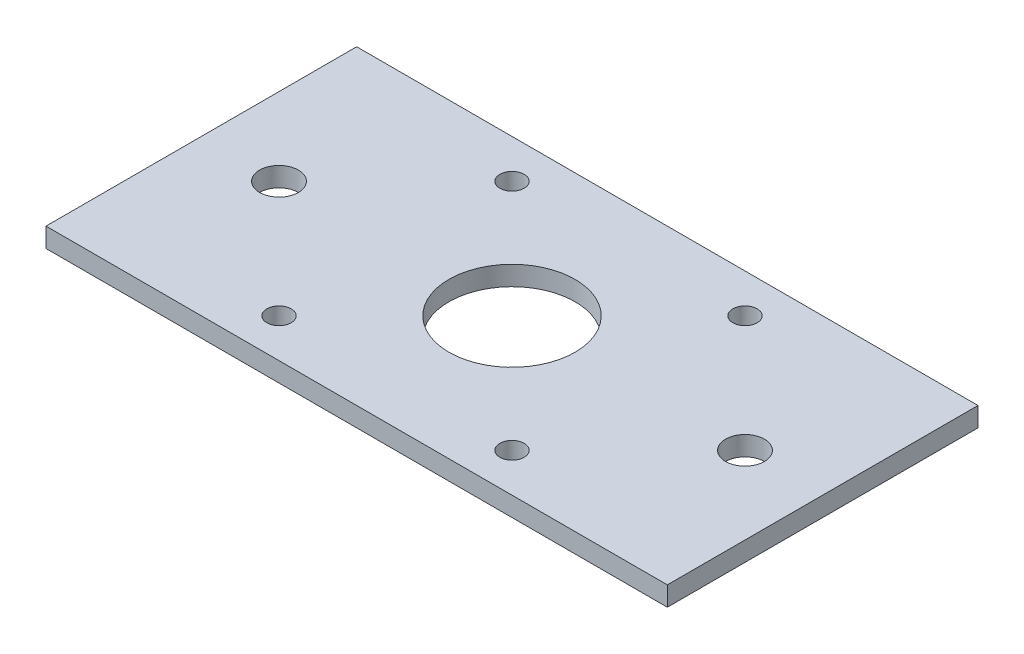
SolidWorks part; units mm, degrees
material "Plain Carbon Steel"
ref_plane "Front Plane" through (0, 0, 0) normal (0, 0, 1) x (1, 0, 0)
ref_plane "Top Plane" through (0, 0, 0) normal (0, 1, 0) x (1, 0, 0)
ref_plane "Right Plane" through (0, 0, 0) normal (1, 0, 0) x (0, 0, -1)
sketch "Sketch1" plane through (0, 0, 0) normal (0, 1, 0) x (1, 0, 0)
  line L1 (-58.7829, -31.8524) -> (144.4171, -31.8524)
  line L2 (-58.7829, -31.8524) -> (-58.7829, 69.7476)
  line L3 (-58.7829, 69.7476) -> (144.4171, 69.7476)
  line L4 (144.4171, -31.8524) -> (144.4171, 69.7476)
  dimension "D1" = 203.2
  dimension "D2" = 101.6
extrude "Boss-Extrude1" add sketch "Sketch1" along normal blind 6.35
sketch "Sketch2" plane through (0, 6.35, 0) normal (0, 1, 0) x (1, 0, 0)
  line L0 (-33.3829, 18.9476) -> (-58.7829, 18.9476) construction
  line L1 (-58.7829, 69.7476) -> (-58.7829, -31.8524) construction
  line L2 (-58.7829, 18.9476) -> (-33.3829, 69.7476) construction
  line L3 (144.4171, 69.7476) -> (-58.7829, 69.7476) construction
  line L4 (-33.3829, 69.7476) -> (-33.3829, 18.9476) construction
  line L5 (-33.3829, 18.9476) -> (119.0171, 18.9476) construction
  line L6 (119.0171, 18.9476) -> (119.0171, 69.7476) construction
  line L7 (119.0171, 69.7476) -> (144.4171, 18.9476) construction
  line L8 (144.4171, -31.8524) -> (144.4171, 69.7476) construction
  line L9 (144.4171, 18.9476) -> (119.0171, 18.9476) construction
  line L10 (-33.3829, 18.9476) -> (-33.3829, -31.8524) construction
  line L11 (-58.7829, -31.8524) -> (144.4171, -31.8524) construction
  line L13 (119.0171, 18.9476) -> (119.0171, -31.8524) construction
  point P0 (-33.3829, 18.9476)
  point P1 (119.0171, 18.9476)
  dimension "D1" = 152.4
hole_wizard "1/2 (0.5) Diameter Hole1" positions "3DSketch1" profile "Sketch3" hole size "1/2" standard "ANSI Inch"
sketch3d "3DSketch1"
  point P0 (-33.3829, 6.35, -18.9476)
  point P3 (119.0171, 6.35, -18.9476)
sketch "Sketch3" plane through (-33.3829, 6.35, -18.9476) normal (1, 0, 0) x (0, 0, 1)
  line L0 (0, 0) -> (0, 29.2155)
  line L1 (0, 29.2155) -> (6.35, 25.4)
  line L2 (6.35, 25.4) -> (6.35, 0)
  line L5 (6.35, 0) -> (0, 0)
  line L10 (0, 29.2155) -> (-6.35, 25.4) construction
  line L11 (0, -6.35) -> (0, 107.95) construction
  dimension "Hole Dia." = 12.7
  dimension "Hole Depth" = 25.4
  dimension "Drill Angle" = 118
sketch "Sketch4" plane through (0, 6.35, 0) normal (0, 1, 0) x (1, 0, 0)
  line L0 (144.4171, 69.7476) -> (-58.7829, 69.7476) construction
  line L1 (-58.7829, 69.7476) -> (-58.7829, -31.8524) construction
  circle A0 centre (42.8171, 18.9476) radius 20.6375
  dimension "D3" = 41.275
  dimension "D1" = 50.8
  dimension "D2" = 101.6
extrude "Cut-Extrude1" cut sketch "Sketch4" against normal through all
sketch "Sketch5" plane through (0, 6.35, 0) normal (0, 1, 0) x (1, 0, 0)
  line L0 (-58.7829, 69.7476) -> (-58.7829, -31.8524) construction
  line L1 (-58.7829, -31.8524) -> (144.4171, -31.8524) construction
  point P0 (4.7171, 57.0476)
  point P1 (80.9171, 57.0476)
  point P2 (80.9171, -19.1524)
  point P3 (4.7171, -19.1524)
  dimension "D1" = 76.2
  dimension "D2" = 76.2
  dimension "D3" = 63.5
  dimension "D4" = 12.7
hole_wizard "3/8-16 Tapped Hole1" positions "3DSketch2" profile "Sketch7" tap size "3/8-16" standard "ANSI Inch"
sketch3d "3DSketch2"
  point P0 (4.7171, 6.35, -57.0476)
  point P3 (80.9171, 6.35, -57.0476)
  point P6 (80.9171, 6.35, 19.1524)
  point P9 (4.7171, 6.35, 19.1524)
sketch "Sketch7" plane through (4.7171, 6.35, -57.0476) normal (1, 0, 0) x (0, 0, 1)
  line L0 (0, 0) -> (0, 26.1972)
  line L1 (0, 26.1972) -> (3.9687, 23.8125)
  line L2 (3.9687, 23.8125) -> (3.9687, 0)
  line L5 (3.9687, 0) -> (0, 0)
  line L10 (0, 26.1972) -> (-3.9688, 23.8125) construction
  line L11 (0, -6.35) -> (0, 107.95) construction
  dimension "Tap Drill Dia." = 7.9375
  dimension "Tap Drill Depth" = 23.8125
  dimension "Drill Angle" = 118
cosmetic thread "Hole Thread1" parameters "D1"=6.35, "D2"=9.525
cosmetic thread "Hole Thread2" parameters "D1"=6.35, "D2"=9.525
cosmetic thread "Hole Thread3" parameters "D1"=6.35, "D2"=9.525
cosmetic thread "Hole Thread4" parameters "D1"=6.35, "D2"=9.525
